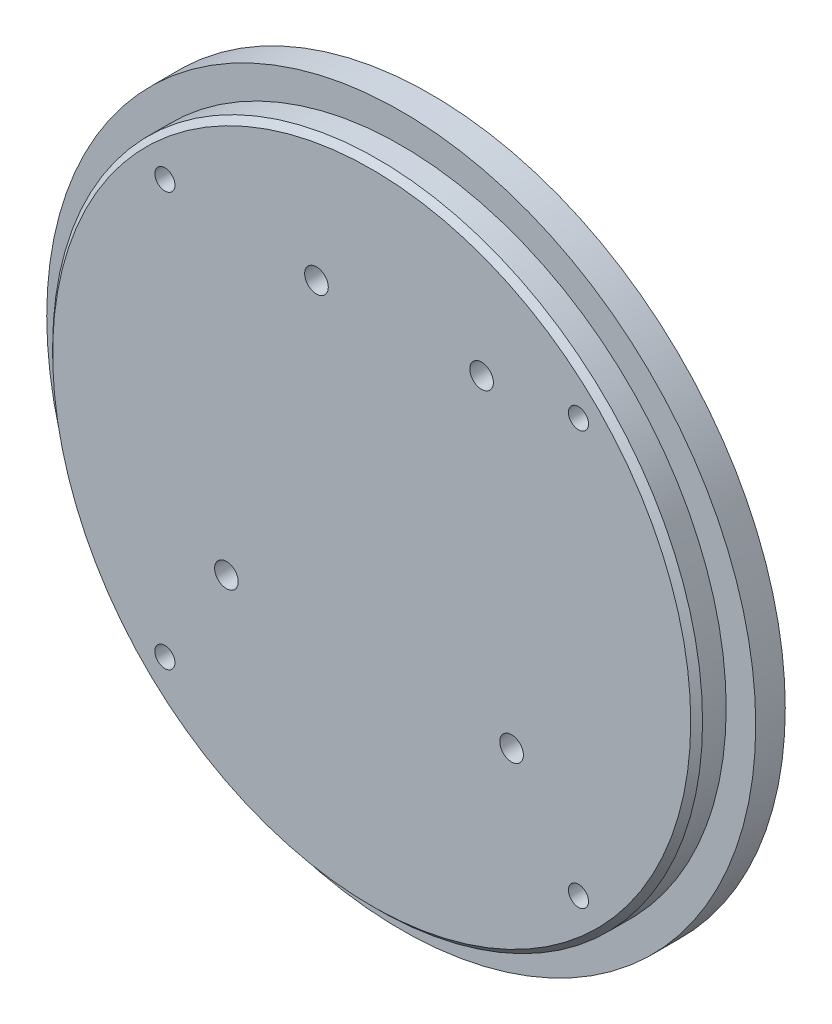
SolidWorks part; units mm, degrees
ref_plane "Front Plane" through (0, 0, 0) normal (0, 0, 1) x (1, 0, 0)
ref_plane "Top Plane" through (0, 0, 0) normal (0, 1, 0) x (1, 0, 0)
ref_plane "Right Plane" through (0, 0, 0) normal (1, 0, 0) x (0, 0, -1)
sketch "Sketch1" plane through (0, 0, 0) normal (0, 0, 1) x (1, 0, 0)
  circle A0 centre (0, 0) radius 55
  dimension "D1" = 110
extrude "Boss-Extrude1" add sketch "Sketch1" against normal blind 10
sketch "Sketch6" plane through (0, 0, -10) normal (0, 0, -1) x (-1, 0, 0)
  circle A0 centre (0, 0) radius 50
  dimension "D1" = 100
extrude "Boss-Extrude3" add sketch "Sketch6" against normal blind 5
sketch "Sketch8" plane through (0, 0, 0) normal (0, 0, 1) x (1, 0, 0)
  circle A0 centre (-9.3439, 33.02) radius 2
  circle A1 centre (18.5961, 33.02) radius 2
  circle A2 centre (-24.5839, -17.78) radius 2
  circle A3 centre (23.6761, -19.05) radius 2
  dimension "D1" = 4
sketch "Sketch9" plane through (0, 0, 0) normal (0, 0, 1) x (1, 0, 0)
  circle A1 centre (23.6761, -19.05) radius 2
  circle A2 centre (23.6761, -19.05) radius 2
  circle A3 centre (-24.5839, -17.78) radius 2
  circle A4 centre (-24.5839, -17.78) radius 2
  circle A5 centre (18.5961, 33.02) radius 2
  circle A6 centre (18.5961, 33.02) radius 2
  circle A7 centre (-9.3439, 33.02) radius 2
  circle A8 centre (-9.3439, 33.02) radius 2
  dimension "D1" = 0
  dimension "D2" = 0
  dimension "D3" = 0
  dimension "D4" = 0
extrude "Cut-Extrude2" cut sketch "Sketch9" against normal blind 8
sketch "Sketch24" plane through (0, 0, -10) normal (0, 0, -1) x (-1, 0, 0)
  circle A0 centre (0, 0) radius 55 construction
  circle A1 centre (0, 0) radius 55
  circle A2 centre (0, 0) radius 60
  dimension "D1" = 5
extrude "Boss-Extrude4" add sketch "Sketch24" against normal blind 5
sketch "Sketch25" plane through (0, 0, -10) normal (0, 0, -1) x (-1, 0, 0)
  line L1 (-35, -35) -> (35, -35) construction
  line L2 (-35, -35) -> (-35, 35) construction
  line L3 (-35, 35) -> (35, 35) construction
  line L4 (35, -35) -> (35, 35) construction
  line L5 (-35, -35) -> (35, 35) construction
  line L6 (-35, 35) -> (35, -35) construction
  point P0 (0, 0)
  point P1 (35, 35)
  point P2 (-35, -35)
  point P3 (-35, 35)
  point P4 (35, -35)
  dimension "D1" = 70
hole_wizard "CBORE for M3 SHCS1" positions "Sketch25" profile "Sketch26" counterbore size "M3" standard "ANSI Metric"
sketch "Sketch26" plane through (-35, -35, -10) normal (1, 0, 0) x (0, 1, 0)
  line L0 (0, 0) -> (0, 10)
  line L1 (0, 10) -> (1.7, 10)
  line L3 (1.7, 10) -> (1.7, 3)
  line L4 (3.25, 3) -> (1.7, 3)
  line L5 (3.25, 3) -> (3.25, 0.025)
  line L6 (3.25, 0.025) -> (3.275, 0)
  line L7 (3.275, 0) -> (0, 0)
  line L8 (-3.25, 0.025) -> (-3.275, 0) construction
  line L11 (0, -6.35) -> (0, 107.95) construction
  dimension "Thru Hole Dia." = 3.4
  dimension "Thru Hole Depth" = 10
  dimension "C'Bore Dia." = 6.5
  dimension "C'Bore Depth" = 3
  dimension "Near C'Sink Dia." = 6.55
  dimension "Near C'Sink Angle" = 90
chamfer "Chamfer2" distance 1 angle 45 1 edges at (55, 0, 0)
